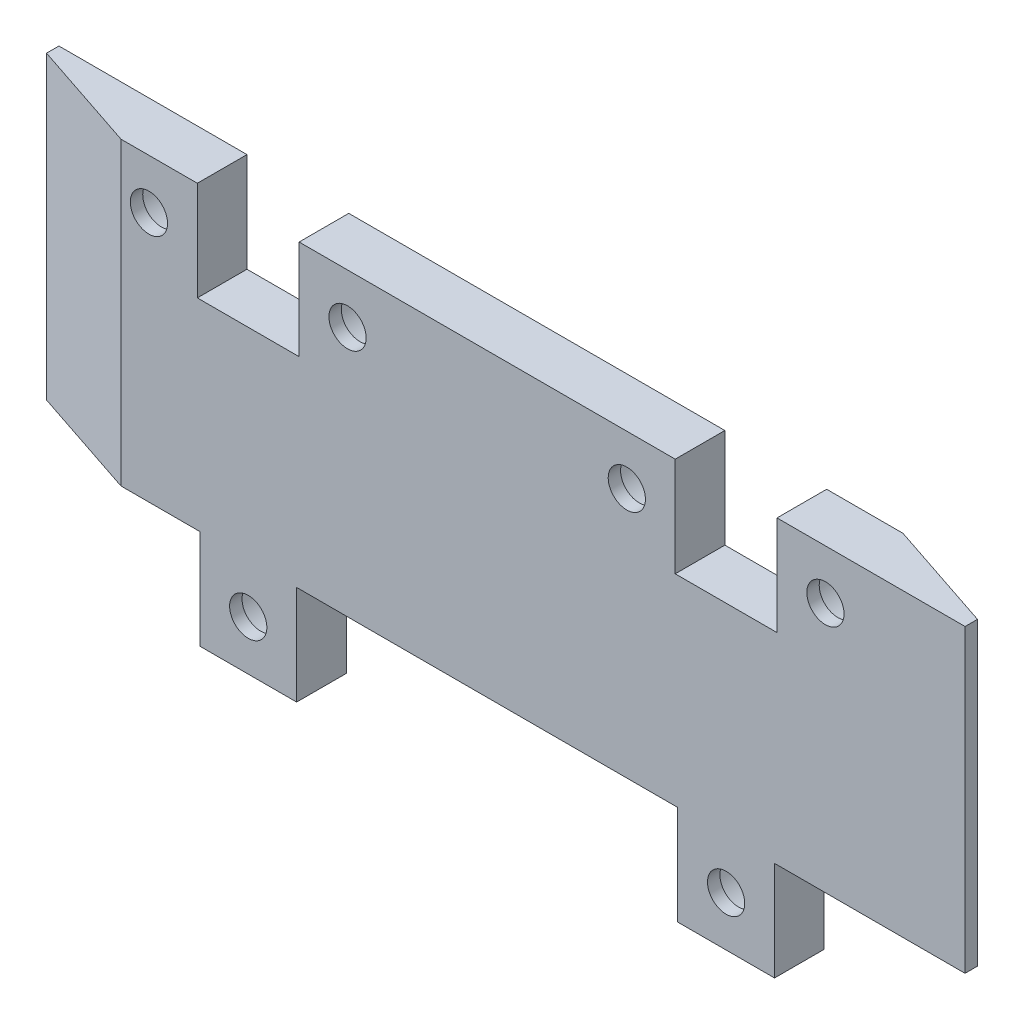
SolidWorks part; units mm, degrees
ref_plane "Front Plane" through (0, 0, 0) normal (0, 0, 1) x (1, 0, 0)
ref_plane "Top Plane" through (0, 0, 0) normal (0, 1, 0) x (1, 0, 0)
ref_plane "Right Plane" through (0, 0, 0) normal (1, 0, 0) x (0, 0, -1)
sketch "草图1" plane through (0, 0, 0) normal (0, 0, 1) x (1, 0, 0)
  line L1 (-38.5, -16.1) -> (38.5, -16.1)
  line L2 (-38.5, -16.1) -> (-38.5, 16.1)
  line L3 (-38.5, 16.1) -> (38.5, 16.1)
  line L4 (38.5, -16.1) -> (38.5, 16.1)
  line L5 (-38.5, -16.1) -> (38.5, 16.1) construction
  line L6 (-38.5, 16.1) -> (38.5, -16.1) construction
  point P0 (0, 0)
  dimension "D1" = 32.2
  dimension "D2" = 77
extrude "凸台-拉伸1" add sketch "草图1" along normal blind 4
sketch "草图4" plane through (0, 0, 0) normal (0, 0, -1) x (-1, 0, 0)
  line L6 (-27.25, 12.1) -> (-11.25, 12.1) construction
  circle A0 centre (-27.25, 12.1) radius 1.5
  circle A1 centre (-19.25, 12.1) radius 1.5
  circle A2 centre (-11.25, 12.1) radius 1.5
  point P0 (-19.25, 12.1)
  point P8 (-19.25, 12.1)
  dimension "D2" = 3
  dimension "D4" = 3
  dimension "D5" = 3
  dimension "D1" = 16
  dimension "D3" = 19.25
  dimension "D6" = 12.1
extrude "切除-拉伸3" cut sketch "草图4" against normal through all
sketch "草图9" plane through (0, 0, 0) normal (0, 0, -1) x (-1, 0, 0)
  circle A0 centre (-27.25, 12.1) radius 3
  circle A1 centre (-19.25, 12.1) radius 3
  circle A2 centre (-11.25, 12.1) radius 3
  dimension "D1" = 6
  dimension "D2" = 6
  dimension "D3" = 6
extrude "切除-拉伸7" cut sketch "草图9" against normal blind 3
pattern_linear "阵列(线性)2" count 2 spacing 38.5 along (-1, 0, 0) of "切除-拉伸3", "切除-拉伸7"
pattern_linear "阵列(线性)3" count 2 spacing 24.2 along (0, -1, 0) of "阵列(线性)2", "切除-拉伸3", "切除-拉伸7"
sketch "草图12" plane through (0, 0, 0) normal (0, 0, 1) x (1, 0, 0)
  line L0 (38.5, 16.1) -> (-38.5, 16.1) construction
  line L1 (-23.35, 16.1) -> (-15.15, 16.1)
  line L2 (-23.35, 16.1) -> (-23.35, 8.1)
  line L3 (-23.35, 8.1) -> (-15.15, 8.1)
  line L4 (-15.15, 16.1) -> (-15.15, 8.1)
  line L5 (-19.25, -988.2415) -> (-19.25, 49011.7585) construction
  line L6 (-38.5, -16.1) -> (38.5, -16.1) construction
  line L7 (-23.15, -16.1) -> (-38.5, -16.1)
  line L8 (-23.15, -16.1) -> (-23.15, -8.1)
  line L9 (-23.15, -8.1) -> (-38.5, -8.1)
  line L10 (-38.5, -16.1) -> (-38.5, -8.1)
  line L11 (-23.15, -8.1) -> (-15.35, -8.1) construction
  line L12 (-15.35, -16.1) -> (0, -16.1)
  line L13 (-15.35, -16.1) -> (-15.35, -8.1)
  line L14 (-15.35, -8.1) -> (0, -8.1)
  line L15 (0, -16.1) -> (0, -8.1)
  point P7 (-19.25, 16.1)
  point P20 (-19.25, 12.1)
  point P21 (-19.25, -8.1)
  dimension "D1" = 8
  dimension "D2" = 8.2
  dimension "D3" = 7.8
  dimension "D4" = 8
  dimension "D5" = 38.5
extrude "切除-拉伸13" cut sketch "草图12" along normal blind 10
pattern_linear "阵列(线性)5" count 2 spacing 38.5 along (1, 0, 0) of "切除-拉伸13"
sketch "草图13" plane through (0, 16.1, 0) normal (0, 1, 0) x (1, 0, 0)
  line L0 (29.5, 0) -> (38.5, 0)
  line L1 (38.5, 0) -> (23.35, 0) construction
  line L2 (38.5, 0) -> (38.5, -3)
  line L3 (38.5, -4) -> (38.5, 0) construction
  line L4 (38.5, -3) -> (29.5, 0)
  line L5 (-38.5, -1) -> (-38.5, -4)
  line L6 (-38.5, -4) -> (-38.5, 0) construction
  line L7 (-38.5, -4) -> (-29.5, -4)
  line L8 (-23.35, -4) -> (-38.5, -4) construction
  line L9 (-29.5, -4) -> (-38.5, -1)
  dimension "D1" = 3
  dimension "D2" = 9
  dimension "D3" = 9
  dimension "D4" = 3
extrude "切除-拉伸14" cut sketch "草图13" against normal through all
